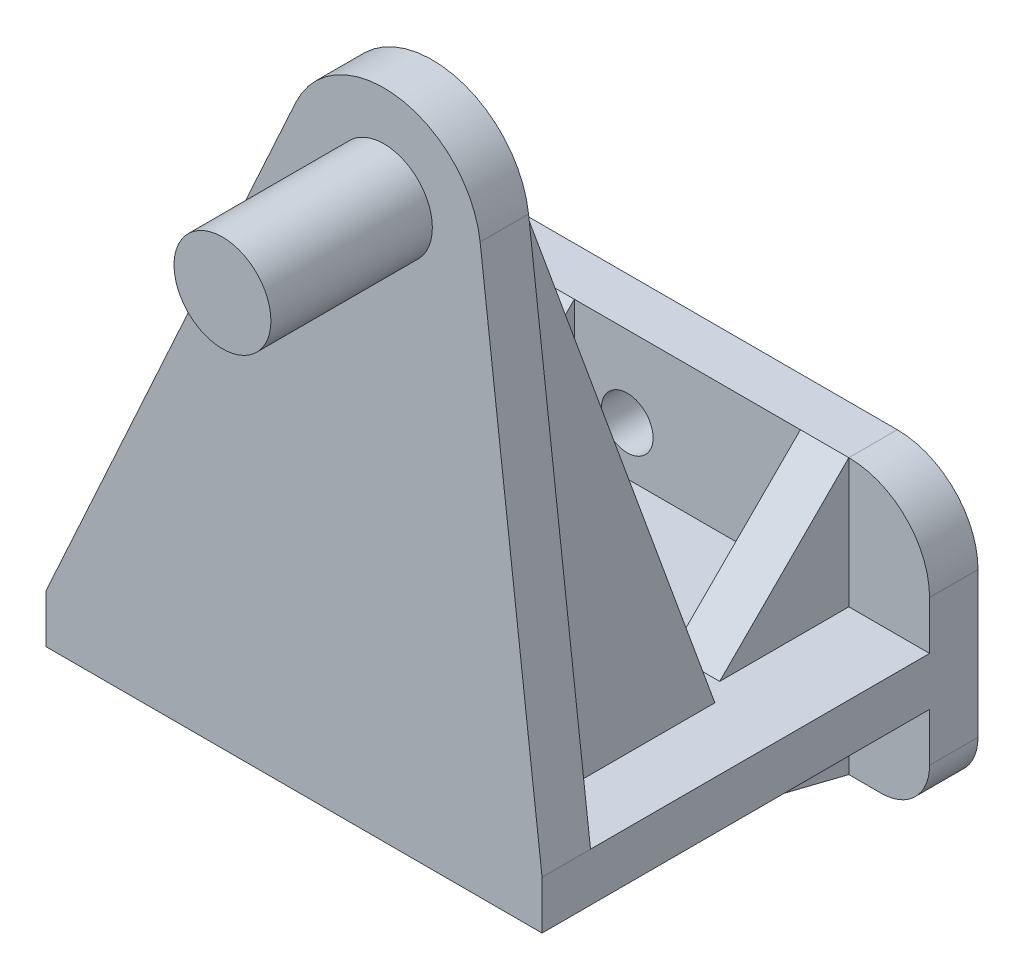
SolidWorks part; units mm, degrees
ref_plane "前视基准面" through (0, 0, 0) normal (0, 0, 1) x (1, 0, 0)
ref_plane "上视基准面" through (0, 0, 0) normal (0, 1, 0) x (1, 0, 0)
ref_plane "右视基准面" through (0, 0, 0) normal (1, 0, 0) x (0, 0, -1)
other "Configuration Table"
sketch "草图1" plane through (0, 0, 0) normal (0, 0, 1) x (1, 0, 0)
  line L0 (0, 0) -> (-10, 0)
  line L1 (-22.2496, 0) -> (16.0464, 0) construction
  line L2 (-15, 0) -> (-15, -6)
  line L3 (-15, -6) -> (5, -6)
  line L4 (5, -6) -> (5, 0)
  line L5 (0, 5) -> (-10, 5)
  line L6 (0, 5) -> (13.7248, 5)
  line L7 (18.7248, 0) -> (18.7248, -6)
  line L8 (18.7248, -6) -> (5, -6)
  line L9 (-15, -6) -> (-15, -9)
  line L10 (-12, -12) -> (15.7248, -12)
  line L11 (18.7248, -9) -> (18.7248, -6)
  circle A0 centre (0, 0) radius 1.6
  circle A1 centre (-10, 0) radius 1.6
  arc A2 (5, 0) -> (0, 5) centre (0, 0) ccw
  arc A3 (-10, 5) -> (-15, 0) centre (-10, 0) ccw
  arc A4 (18.7248, 0) -> (13.7248, 5) centre (13.7248, 0) ccw
  arc A5 (18.7248, -9) -> (15.7248, -12) centre (15.7248, -9) cw
  arc A6 (-12, -12) -> (-15, -9) centre (-12, -9) cw
  dimension "D2" = 3.2
  dimension "D3" = 3.2
  dimension "D5" = 5
  dimension "D7" = 5
  dimension "D9" = 3
  dimension "D1" = 10
  dimension "D4" = 0
  dimension "D6" = 6
  dimension "D8" = 6
extrude "凸台-拉伸1" add sketch "草图1" along normal blind 3
sketch "草图2" plane through (0, 0, 3) normal (0, 0, 1) x (1, 0, 0)
  line L1 (-12, -3) -> (18.7248, -3)
  line L2 (-12, -3) -> (-12, -6)
  line L3 (-12, -6) -> (18.7248, -6)
  line L4 (18.7248, -3) -> (18.7248, -6)
  line L5 (55, 0) -> (-55, 0) construction
  line L6 (18.7248, 0) -> (18.7248, -9) construction
  line L7 (-15, 0) -> (-15, -9) construction
  dimension "D1" = 3
  dimension "D2" = 6
  dimension "D3" = 3
extrude "凸台-拉伸2" add sketch "草图2" along normal blind 24
ref_plane "基准面1" through (0, 0, 27) normal (0, 0, 1) x (1, 0, 0)
sketch "草图4" plane through (0, 0, 27) normal (0, 0, 1) x (1, 0, 0)
  circle A0 centre (8.93, 28.44) radius 3
  dimension "D1" = 6
  dimension "D2" = 8.93
  dimension "D3" = 28.44
extrude "凸台-拉伸3" add sketch "草图4" along normal blind 10 separate body
sketch "草图5" plane through (0, 0, 27) normal (0, 0, -1) x (-1, 0, 0)
  line L0 (-3.4707, 30.9293) -> (12, -3)
  line L2 (12, -3) -> (-18.7248, -3)
  line L3 (-18.7248, -3) -> (-14.8877, 29.151)
  line L4 (12, -3) -> (12, -6) construction
  line L5 (-18.7248, -3) -> (12, -3) construction
  circle A0 centre (-8.93, 28.44) radius 6
  circle M3 centre (-8.93, 28.44) radius 3
  dimension "D1" = 12
  dimension "D2" = 30.7248
extrude "凸台-拉伸4" add sketch "草图5" along normal blind 3 contours A0 L3 L2 L0 | A0 M3 | M3
sketch "草图6" plane through (18.7248, 0, 0) normal (1, 0, 0) x (0, 0, -1)
  line L0 (-24, 29.151) -> (-12.298, -3)
  line L1 (-24, -3) -> (-24, 29.151) construction
  line L2 (-24, -3) -> (-3, -3) construction
  line L3 (-12.298, -3) -> (-24, -3)
  line L4 (-24, -3) -> (-24, 29.151)
  dimension "D1" = 20
extrude "凸台-拉伸5" add sketch "草图6" against normal blind 3 from offset 4 offset against normal yes
sketch "草图7" plane through (18.7248, 0, 0) normal (1, 0, 0) x (0, 0, -1)
  line L0 (-24, 19.0086) -> (-15.9895, -3)
  line L3 (-12.298, -3) -> (-24, 29.151)
  line L4 (-24, -3) -> (-12.298, -3)
  line L5 (-24, 29.151) -> (-24, -3)
  line L6 (-12.298, -3) -> (-24, 29.151)
  line L7 (-24, -3) -> (-12.298, -3)
  line L8 (-24, 29.151) -> (-24, -3)
  line M8 (-3, -3) -> (-24, -3)
  dimension "D1" = 0
extrude "凸台-拉伸6" add sketch "草图7" along normal blind 3 from offset 18 contours L0 L8 M8 offset against normal yes
sketch "草图8" plane through (18.7248, 0, 0) normal (1, 0, 0) x (0, 0, -1)
  line L0 (-3, 5) -> (-11, -3)
  line L1 (-24, -3) -> (-3, -3) construction
  line L2 (-11, -3) -> (-3, -3)
  line L3 (-3, -3) -> (-3, 5)
  line L4 (-3, -12) -> (-27, -6)
  line L5 (-27, -6) -> (-3, -6) construction
  line L6 (-27, -6) -> (-3, -6)
  line L7 (-3, -6) -> (-3, -12)
  line L8 (-27, 1.65) -> (-27, -1.65) construction
  dimension "D1" = 45
extrude "凸台-拉伸7" add sketch "草图8" against normal blind 3 from offset 5 offset against normal yes
sketch "草图9" plane through (18.7248, 0, 0) normal (1, 0, 0) x (0, 0, -1)
  line L3 (-27, -6) -> (-3, -12)
  line L4 (-3, -6) -> (-27, -6)
  line L5 (-3, -12) -> (-3, -6)
  line L6 (-27, -6) -> (-3, -12)
  line L7 (-3, -6) -> (-27, -6)
  line L8 (-3, -12) -> (-3, -6)
  line L9 (-3, 5) -> (-11, -3)
  line L10 (-11, -3) -> (-3, -3)
  line L11 (-3, -3) -> (-3, 5)
  line L12 (-3, 5) -> (-11, -3)
  line L13 (-11, -3) -> (-3, -3)
  line L14 (-3, -3) -> (-3, 5)
  dimension "D1" = 0
  dimension "D2" = 0
extrude "凸台-拉伸8" add sketch "草图9" against normal blind 3 from offset 22
